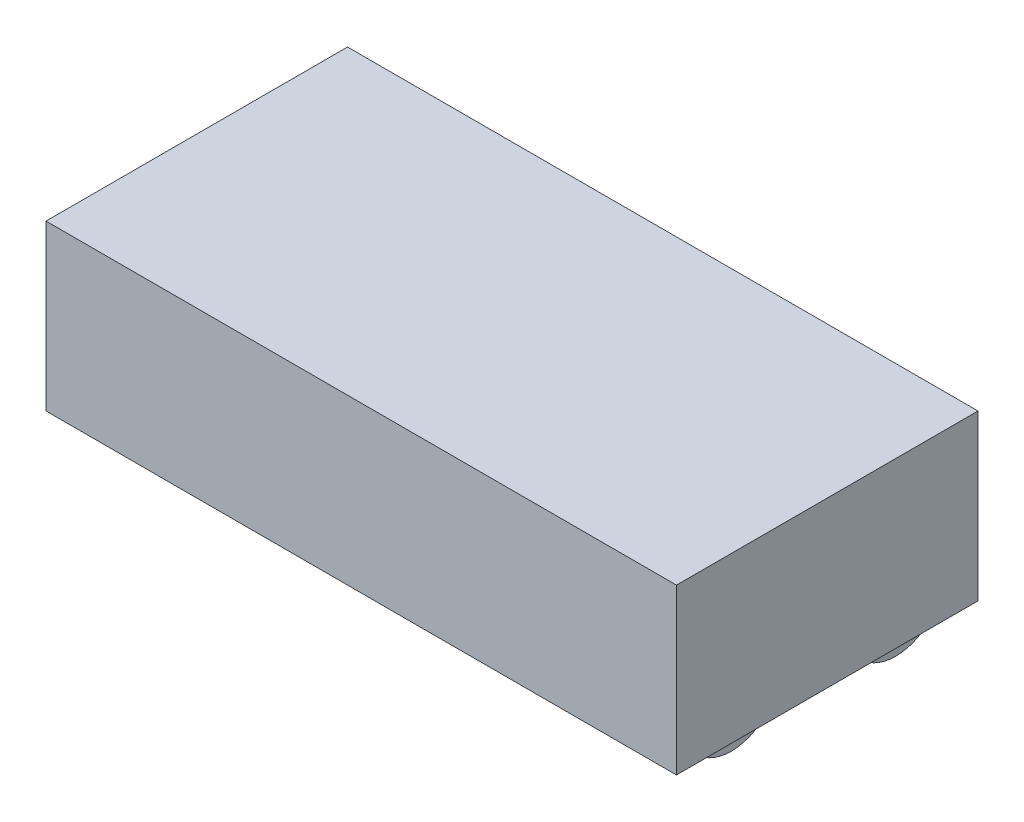
SolidWorks part; units mm, degrees
ref_plane "Front Plane" through (0, 0, 0) normal (0, 0, 1) x (1, 0, 0)
ref_plane "Top Plane" through (0, 0, 0) normal (0, 1, 0) x (1, 0, 0)
ref_plane "Right Plane" through (0, 0, 0) normal (1, 0, 0) x (0, 0, -1)
sketch "Chasis" plane through (0, 0, 0) normal (0, 1, 0) x (1, 0, 0)
  line L1 (-292.1, -139.7) -> (292.1, -139.7)
  line L2 (-292.1, -139.7) -> (-292.1, 139.7)
  line L3 (-292.1, 139.7) -> (292.1, 139.7)
  line L4 (292.1, -139.7) -> (292.1, 139.7)
  line L5 (-292.1, -139.7) -> (292.1, 139.7) construction
  line L6 (-292.1, 139.7) -> (292.1, -139.7) construction
  point P0 (0, 0)
  dimension "D1" = 584.2
  dimension "D2" = 279.4
extrude "Boss-Extrude1" add sketch "Chasis" along normal blind 152.4 contours L3 L4 L1 L2
ref_plane "Plane1" through (0, 25.4, 0) normal (0, -1, 0) x (-1, 0, 0)
sketch "Sketch3" plane through (0, 25.4, 0) normal (0, -1, 0) x (-1, 0, 0)
  line L0 (279.4, -76.2) -> (234.95, -76.2)
  line L1 (279.4, -76.2) -> (279.4, -120.65)
  line L2 (279.4, -120.65) -> (234.95, -120.65)
  line L3 (234.95, -76.2) -> (234.95, -120.65)
  line L4 (292.1, -139.7) -> (292.1, 139.7) construction
  line L5 (292.1, -139.7) -> (-292.1, -139.7) construction
  dimension "D1" = 44.45
  dimension "D2" = 44.45
  dimension "D3" = 12.7
  dimension "D4" = 19.05
revolve "Revolve1" add sketch "Sketch3" angle 360 about L0
mirror "Mirror1" about plane through (0, 0, 0) normal (0, 0, 1) of "Revolve1"
mirror "Mirror2" about plane through (0, 0, 0) normal (1, 0, 0) of "Revolve1", "Mirror1"
